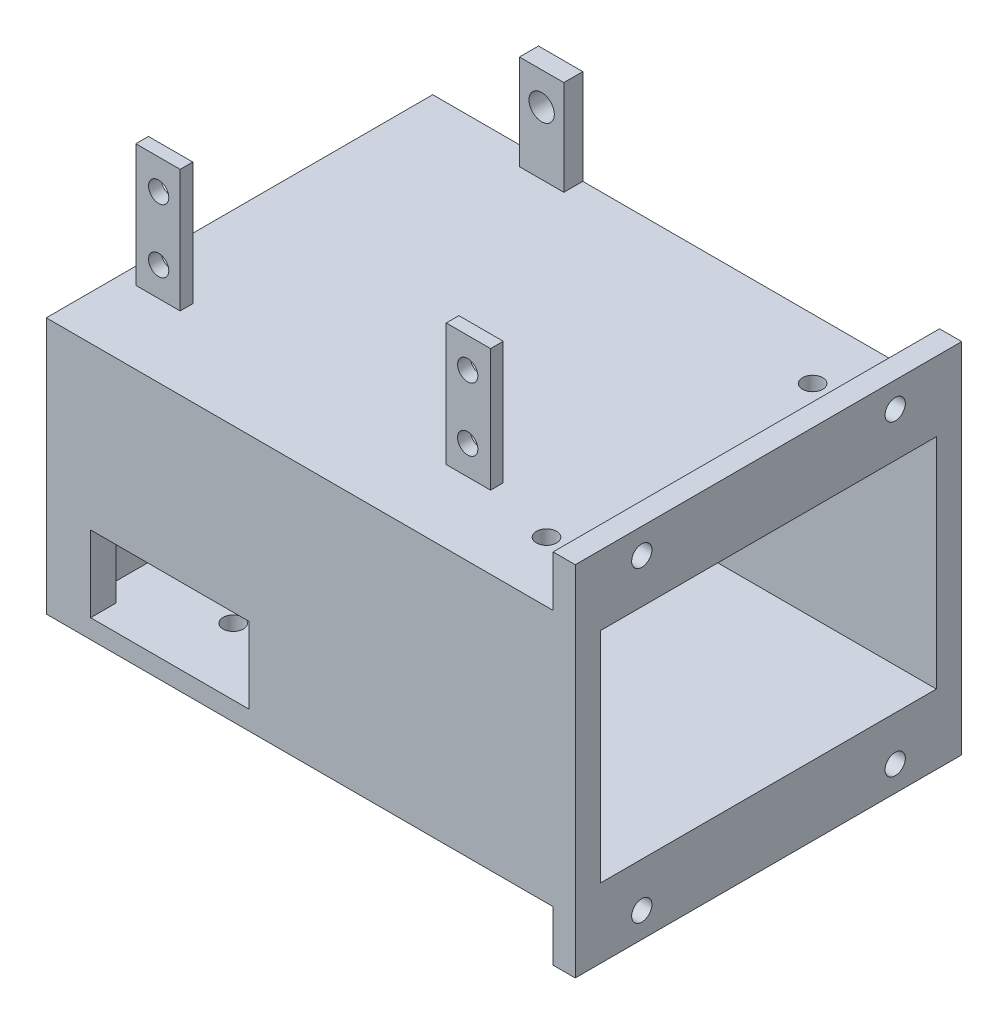
SolidWorks part; units mm, degrees
ref_plane "정면" through (0, 0, 0) normal (0, 0, 1) x (1, 0, 0)
ref_plane "윗면" through (0, 0, 0) normal (0, 1, 0) x (1, 0, 0)
ref_plane "우측면" through (0, 0, 0) normal (1, 0, 0) x (0, 0, -1)
sketch "Sketch1" plane through (0, 0, 0) normal (0, 1, 0) x (1, 0, 0)
  line L0 (-75.5, 30.5) -> (75.5, 30.5)
  line L1 (-71.5, 26.5) -> (71.5, 26.5)
  line L2 (-71.5, 26.5) -> (-71.5, -26.5)
  line L3 (-71.5, -26.5) -> (71.5, -26.5)
  line L4 (71.5, 26.5) -> (71.5, -26.5)
  line L5 (-71.5, 26.5) -> (71.5, -26.5) construction
  line L6 (-71.5, -26.5) -> (71.5, 26.5) construction
  line L7 (75.5, 30.5) -> (75.5, -30.5)
  line L8 (-75.5, -30.5) -> (75.5, -30.5)
  line L9 (-75.5, 30.5) -> (-75.5, -30.5)
  point P0 (0, 0)
  dimension "D1" = 143
  dimension "D2" = 53
  dimension "D3" = 4
extrude "Boss-Extrude1" add sketch "Sketch1" along normal mid plane 40.5
sketch "Sketch2" plane through (0, -20.25, 0) normal (0, -1, 0) x (1, 0, 0)
  line L1 (-71.5, 26.5) -> (71.5, 26.5)
  line L2 (-71.5, 26.5) -> (-71.5, -26.5)
  line L3 (-71.5, -26.5) -> (71.5, -26.5)
  line L4 (71.5, 26.5) -> (71.5, -26.5)
extrude "Boss-Extrude2" add sketch "Sketch2" against normal blind 3
sketch "Sketch7" plane through (75.5, 0, 0) normal (1, 0, 0) x (0, 0, -1)
  line L0 (-30.5, 20.25) -> (30.5, 20.25) construction
  line L1 (-26.5, 20.25) -> (26.5, 20.25)
  line L2 (-26.5, 20.25) -> (-26.5, -17.25)
  line L3 (-26.5, -17.25) -> (26.5, -17.25)
  line L4 (26.5, 20.25) -> (26.5, -17.25)
  line L6 (26.5, -17.25) -> (-26.5, -17.25) construction
  line L7 (26.5, -17.25) -> (-26.5, -17.25) construction
  point P7 (0, 20.25)
  dimension "D2" = 53
extrude "Cut-Extrude3" cut sketch "Sketch7" against normal blind 4 contours L4 L3 L2 L1
sketch "Sketch9" plane through (0, 20.25, 0) normal (0, 1, 0) x (1, 0, 0)
  line L0 (-71.5, -26.5) -> (-71.5, 26.5) construction
  line L1 (-71.5, 26.5) -> (75.5, 26.5) construction
  line L2 (75.5, -26.5) -> (-71.5, -26.5) construction
  line L3 (75.5, -26.5) -> (75.5, 26.5) construction
  line L4 (-71.5, -26.5) -> (-71.5, 26.5)
  line L5 (-71.5, 26.5) -> (75.5, 26.5)
  line L6 (75.5, -26.5) -> (-71.5, -26.5)
  line L7 (75.5, -26.5) -> (75.5, 26.5)
extrude "Boss-Extrude3" add sketch "Sketch9" against normal blind 3
sketch "Sketch10" plane through (0, 20.25, 0) normal (0, 1, 0) x (1, 0, 0)
  line L0 (-75.5, 0) -> (75.5, 0) construction
  line L1 (-75.5, 30.5) -> (-75.5, -30.5) construction
  line L2 (75.5, -30.5) -> (75.5, 30.5) construction
  line L3 (60, 0) -> (60, 24.1) construction
  line L4 (-6.04, 0) -> (-6.04, 21) construction
  circle A0 centre (60, 24.1) radius 1.6
  circle A1 centre (60, -24.1) radius 1.6
  circle A2 centre (-6.04, 21) radius 1.6
  circle A3 centre (-6.04, -21) radius 1.6
  dimension "D2" = 3.2
  dimension "D5" = 3.2
  dimension "D1" = 24.1
  dimension "D3" = 15.5
  dimension "D4" = 21
  dimension "D6" = 66.04
extrude "Cut-Extrude4" cut sketch "Sketch10" against normal up to next
sketch "Sketch12" plane through (0, 0, 30.5) normal (0, 0, 1) x (1, 0, 0)
  line L0 (75.5, 0) -> (-31.9096, 0) construction
  line L1 (75.5, 20.25) -> (75.5, -20.25) construction
  line L2 (67.4452, 4.65) -> (67.4452, -4.65) construction
  line L3 (67.4452, 4.65) -> (17.5452, 4.65) construction
  circle A0 centre (67.4452, 4.65) radius 1.55
  circle A1 centre (67.4452, -4.65) radius 1.55
  circle A2 centre (17.5452, 4.65) radius 1.55
  circle A3 centre (17.5452, -4.65) radius 1.55
  point P7 (67.4452, 0)
  dimension "D2" = 49.9
  dimension "D3" = 3.1
  dimension "D4" = 3.1
  dimension "D1" = 9.3
extrude "Cut-Extrude6" cut sketch "Sketch12" against normal through all
ref_plane "Plane1" through (0, 0, 17) normal (0, 0, 1) x (1, 0, 0)
sketch "Sketch13" plane through (0, 0, 17) normal (0, 0, 1) x (1, 0, 0)
  line L0 (-75.5, 20.25) -> (-75.5, -20.25) construction
  line L1 (-72.87, 20.25) -> (-65.87, 20.25)
  line L2 (-72.87, 20.25) -> (-72.87, 39.61)
  line L3 (-72.87, 39.61) -> (-65.87, 39.61)
  line L4 (-65.87, 20.25) -> (-65.87, 39.61)
  line L6 (-75.5, 20.25) -> (75.5, 20.25) construction
  dimension "D1" = 2.63
  dimension "D2" = 7
  dimension "D3" = 19.36
extrude "Boss-Extrude4" add sketch "Sketch13" along normal blind 2
sketch "Sketch16" plane through (0, 0, 19) normal (0, 0, 1) x (1, 0, 0)
  line L0 (-69.2622, 20.25) -> (-69.2622, 39.61) construction
  line L3 (-75.5, 20.25) -> (75.5, 20.25) construction
  line L4 (-72.87, 20.25) -> (-65.87, 20.25) construction
  line L5 (-65.87, 39.61) -> (-72.87, 39.61) construction
  circle A0 centre (-69.2622, 24.85) radius 1.6
  circle A1 centre (-69.2622, 34.85) radius 1.6
  point P8 (-69.2622, 23.25)
  point P11 (-69.2622, 34.85)
  dimension "D1" = 3.2
  dimension "D4" = 3.2
  dimension "D2" = 3
  dimension "D3" = 10
extrude "Cut-Extrude7" cut sketch "Sketch16" against normal blind 10
ref_plane "Plane3" through (-65.87, 0, 0) normal (1, 0, 0) x (0, 0, -1)
ref_plane "Plane4" through (-44.87, 0, 0) normal (1, 0, 0) x (0, 0, -1)
mirror "Mirror1" about plane through (-44.87, 0, 0) normal (1, 0, 0) of "Cut-Extrude7", "Boss-Extrude4"
sketch "Sketch17" plane through (0, 0, -30.5) normal (0, 0, -1) x (-1, 0, 0)
  line L0 (-75.5, 20.25) -> (75.5, 20.25) construction
  line L1 (58.81, 20.25) -> (51.81, 20.25)
  line L2 (58.81, 20.25) -> (58.81, 35.25)
  line L3 (58.81, 35.25) -> (51.81, 35.25)
  line L4 (51.81, 20.25) -> (51.81, 35.25)
  line L5 (55.31, 20.25) -> (55.31, 35.25) construction
  line L6 (75.5, 20.25) -> (75.5, -20.25) construction
  circle A0 centre (55.31, 30.15) radius 2
  point P8 (55.31, 30.15)
  dimension "D2" = 4
  dimension "D1" = 9.9
  dimension "D3" = 20.19
  dimension "D4" = 7
  dimension "D5" = 15
extrude "Boss-Extrude5" add sketch "Sketch17" against normal blind 3
sketch "Sketch18" plane through (0, -20.25, 0) normal (0, -1, 0) x (1, 0, 0)
  line L0 (-56.5, 30.5) -> (-56.5, -30.5) construction
  line L1 (-75.5, 30.5) -> (75.5, 30.5) construction
  line L2 (75.5, -30.5) -> (-75.5, -30.5) construction
  line L3 (-75.5, 0) -> (75.5, 0) construction
  line L4 (-75.5, -30.5) -> (-75.5, 30.5) construction
  line L5 (75.5, 30.5) -> (75.5, -30.5) construction
  circle A0 centre (-56.5, 20) radius 1.6
  circle A1 centre (-56.5, -20) radius 1.6
  point P12 (-56.5, 20)
  point P13 (-56.5, -20)
  dimension "D3" = 19
  dimension "D1" = 20
  dimension "D2" = 20
extrude "Cut-Extrude8" cut sketch "Sketch18" against normal blind 10
sketch "Sketch19" plane through (0, 0, 30.5) normal (0, 0, 1) x (1, 0, 0)
  line L1 (-68.5, -17.25) -> (-43.5, -17.25)
  line L2 (-68.5, -17.25) -> (-68.5, -5.25)
  line L3 (-68.5, -5.25) -> (-43.5, -5.25)
  line L4 (-43.5, -17.25) -> (-43.5, -5.25)
  line L5 (-75.5, 20.25) -> (-75.5, -20.25) construction
  dimension "D1" = 7
  dimension "D2" = 25
  dimension "D3" = 12
extrude "Cut-Extrude9" cut sketch "Sketch19" against normal through all
sketch "Sketch20" plane through (0, 20.25, 0) normal (0, 1, 0) x (1, 0, 0)
  line L0 (-75.5, -30.5) -> (75.5, -30.5) construction
  line L1 (4.5, -30.5) -> (11.5, -30.5)
  line L2 (4.5, -30.5) -> (4.5, 30.5)
  line L3 (4.5, 30.5) -> (11.5, 30.5)
  line L4 (11.5, -30.5) -> (11.5, 30.5)
  line L5 (75.5, 30.5) -> (-51.81, 30.5) construction
  line L6 (-75.5, 30.5) -> (-75.5, -30.5) construction
  dimension "D1" = 7
  dimension "D2" = 80
extrude "Boss-Extrude6" add sketch "Sketch20" along normal blind 8
sketch "Sketch21" plane through (4.5, 0, 0) normal (-1, 0, 0) x (0, 0, 1)
  line L0 (30.5, 24.25) -> (-30.5, 24.25) construction
  line L1 (30.5, 28.25) -> (30.5, 20.25) construction
  line L2 (-30.5, 20.25) -> (-30.5, 35.25) construction
  line L3 (0, 28.25) -> (0, 20.25) construction
  line L4 (-30.5, 28.25) -> (30.5, 28.25) construction
  line L5 (-30.5, 20.25) -> (30.5, 20.25) construction
  circle A0 centre (-20, 24.25) radius 1.6
  circle A1 centre (20, 24.25) radius 1.6
  dimension "D1" = 20
extrude "Cut-Extrude10" cut sketch "Sketch21" against normal up to next
mirror "Mirror2" about plane through (0, 0, 0) normal (0, 1, 0) of "Cut-Extrude10", "Boss-Extrude6"
sketch "Sketch22" plane through (0, 0, 0) normal (0, 1, 0) x (1, 0, 0)
  line L1 (8, 36.9778) -> (83.4302, 36.9778)
  line L2 (8, 36.9778) -> (8, -36.9777)
  line L3 (8, -36.9777) -> (83.4302, -36.9777)
  line L4 (83.4302, 36.9778) -> (83.4302, -36.9777)
  line L5 (-75.5, 30.5) -> (-75.5, -30.5) construction
  dimension "D1" = 83.5
extrude "Cut-Extrude11" cut sketch "Sketch22" against normal through all both and the other way through all
